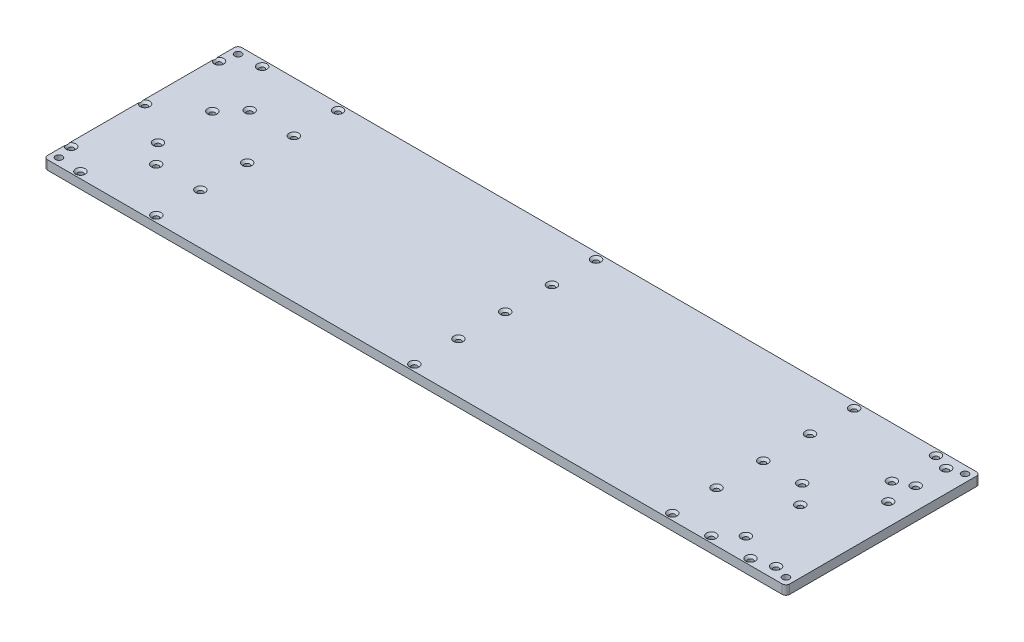
SolidWorks part; units mm, degrees
material "6061 Alloy"
ref_plane "Front Plane" through (0, 0, 0) normal (0, 0, 1) x (1, 0, 0)
ref_plane "Top Plane" through (0, 0, 0) normal (0, 1, 0) x (1, 0, 0)
ref_plane "Right Plane" through (0, 0, 0) normal (1, 0, 0) x (0, 0, -1)
sketch "Sketch1" plane through (0, 0, 0) normal (0, 1, 0) x (1, 0, 0)
  line L1 (-244.475, 64) -> (244.475, 64)
  line L2 (-244.475, 64) -> (-244.475, -64)
  line L3 (-244.475, -64) -> (244.475, -64)
  line L4 (244.475, 64) -> (244.475, -64)
  line L5 (-244.475, 64) -> (244.475, -64) construction
  line L6 (-244.475, -64) -> (244.475, 64) construction
  point P0 (0, 0)
  dimension "D1" = 128
  dimension "D2" = 488.95
extrude "Boss-Extrude1" add sketch "Sketch1" along normal blind 6
hole_wizard "M4 Clearance Hole1" positions "Sketch2" profile "Sketch3" hole size "M4" standard "ANSI Metric"
sketch "Sketch2" plane through (0, 6, 0) normal (0, 1, 0) x (1, 0, 0)
  line L0 (239.475, 59) -> (239.475, -59) construction
  line L1 (239.475, -59) -> (-239.475, -59) construction
  line L2 (-239.475, -59) -> (-239.475, 59) construction
  line L3 (-239.475, 59) -> (239.475, 59) construction
  line L6 (244.475, 64) -> (-244.475, 64) construction
  line L7 (-244.475, 64) -> (-244.475, -64) construction
  line L8 (-244.475, -64) -> (244.475, -64) construction
  line L9 (244.475, -64) -> (244.475, 64) construction
  point P0 (-239.475, 59)
  point P2 (-239.475, -59)
  point P4 (239.475, -59)
  point P6 (239.475, 59)
  dimension "D1" = 5
  dimension "D2" = 5
  dimension "D3" = 5
  dimension "D4" = 5
sketch "Sketch3" plane through (-239.475, 6, -59) normal (1, 0, 0) x (0, 0, 1)
  line L0 (0, 0) -> (0, 18.7319)
  line L1 (0, 18.7319) -> (2.25, 17.38)
  line L2 (2.25, 17.38) -> (2.25, 0)
  line L5 (2.25, 0) -> (0, 0)
  line L10 (0, 18.7319) -> (-2.25, 17.38) construction
  line L11 (0, -6.35) -> (0, 107.95) construction
  dimension "Hole Dia." = 4.5
  dimension "Hole Depth" = 17.38
  dimension "Drill Angle" = 118
fillet "Fillet1" radius 2.5 4 edges at (244.475, 3, -64) (244.475, 3, 64) (-244.475, 3, -64) (-244.475, 3, 64)
hole_wizard "CSK for M3 Flat Head Machine Screw1" positions "Sketch4" profile "Sketch5" countersink size "M3" standard "ANSI Metric"
sketch "Sketch4" plane through (0, 6, 0) normal (0, 1, 0) x (1, 0, 0)
  point P0 (-241.725, 0)
  point P3 (-241.725, -48.7)
  point P6 (-224.475, -59.85)
  point P9 (-174.475, -59.85)
  point P12 (-203.675, -30.8)
  point P15 (-215.325, -17.9)
  point P18 (-215.325, 17.9)
  point P21 (-203.675, 30.8)
  point P24 (-224.475, 59.85)
  point P27 (-241.725, 48.7)
  point P30 (-4.475, -59.85)
  point P33 (165.525, -59.85)
  point P36 (202.825, -48.7)
  point P39 (191.175, -59.85)
  point P42 (216.975, -59.85)
  point P45 (229.975, -56)
  point P48 (-174.475, 0)
  point P51 (-174.475, 30.8)
  point P54 (-174.475, -30.8)
  point P57 (-174.475, 59.85)
  point P60 (-4.475, 59.85)
  point P63 (165.525, 59.85)
  point P66 (229.975, 36)
  point P69 (219.475, 59.85)
  point P72 (229.975, 56)
  point P75 (165.525, 30.8)
  point P78 (191.175, 0)
  point P81 (202.825, -12.9)
  point P84 (165.525, 0)
  point P87 (229.975, 17.9)
  point P90 (219.475, 30.8)
  point P93 (165.525, -30.8)
  point P96 (-4.475, 30.8)
  point P99 (-4.475, 0)
  point P102 (-4.475, -30.8)
sketch "Sketch5" plane through (-241.725, 6, 0) normal (1, 0, 0) x (0, 0, 1)
  line L0 (0, 0) -> (0, 11.0215)
  line L1 (0, 11.0215) -> (1.7, 10)
  line L2 (1.7, 10) -> (1.7, 1.45)
  line L3 (1.7, 1.45) -> (3.15, 0)
  line L5 (3.15, 0) -> (0, 0)
  line L6 (-1.7, 1.45) -> (-3.15, 0) construction
  line L10 (0, 11.0215) -> (-1.7, 10) construction
  line L11 (0, -6.35) -> (0, 107.95) construction
  dimension "Hole Dia." = 3.4
  dimension "Hole Depth" = 10
  dimension "Near C'Sink Dia." = 6.3
  dimension "Near C'Sink Angle" = 90
  dimension "Drill Angle" = 118
